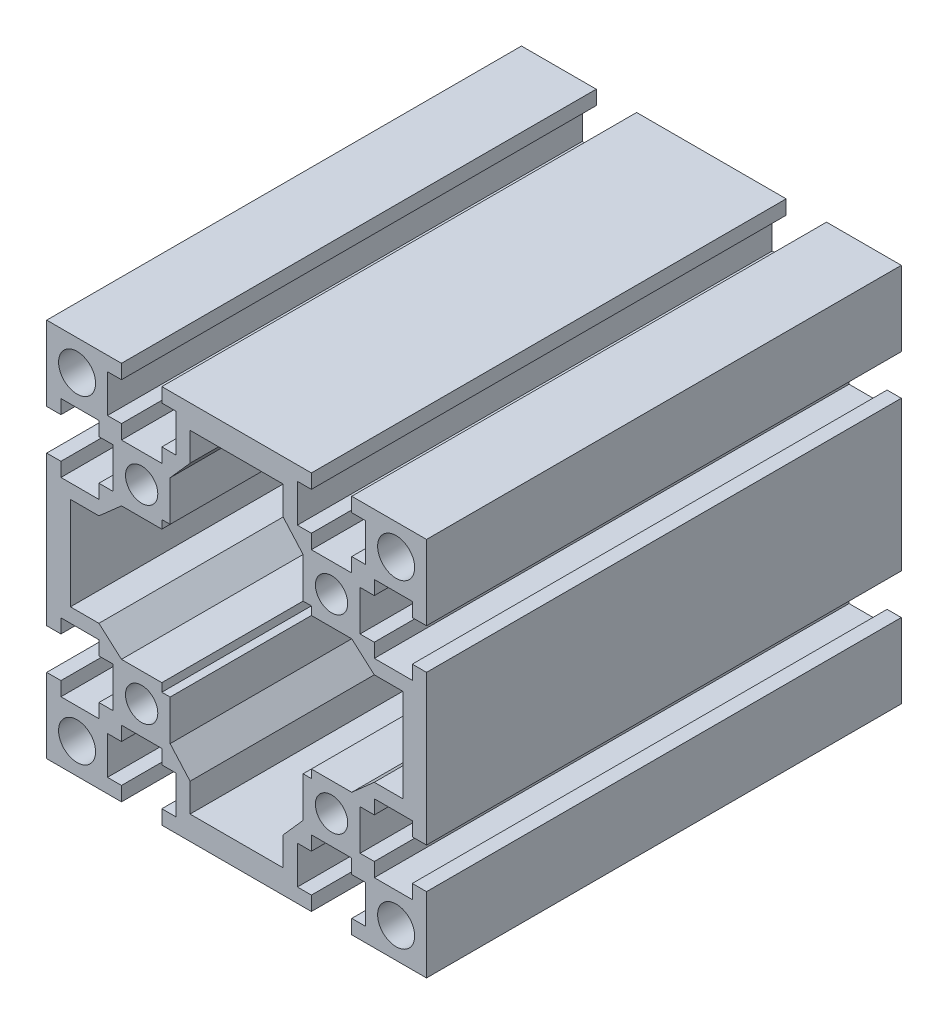
SolidWorks part; units mm, degrees
ref_plane "前视基准面" through (0, 0, 0) normal (0, 0, 1) x (1, 0, 0)
ref_plane "上视基准面" through (0, 0, 0) normal (0, 1, 0) x (1, 0, 0)
ref_plane "右视基准面" through (0, 0, 0) normal (1, 0, 0) x (0, 0, -1)
sketch "草图1" plane through (0, 0, 0) normal (0, 0, 1) x (1, 0, 0)
  line L0 (-23.2188, 39.5458) -> (-38.9688, 39.5458)
  line L1 (-38.9688, 39.5458) -> (-38.9688, 23.7958)
  line L2 (-23.2188, 36.5458) -> (-26.1688, 36.5458)
  line L3 (-35.9688, 26.7458) -> (-35.9688, 23.7958)
  line L4 (-24.9688, 23.7958) -> (-24.9688, 15.2958)
  line L5 (-23.2188, 13.5458) -> (-14.7188, 13.5458)
  line L6 (-12.9688, 15.2958) -> (-12.9688, 23.7958)
  line L7 (-14.7188, 25.5458) -> (-23.2188, 25.5458)
  line L8 (-27.9688, 26.7458) -> (-27.9688, 23.7958)
  line L9 (-23.2188, 28.5458) -> (-26.1688, 28.5458)
  line L10 (-35.9688, 26.7458) -> (-27.9688, 26.7458)
  line L11 (-38.9688, 23.7958) -> (-35.9688, 23.7958)
  line L12 (-27.9688, 23.7958) -> (-24.9688, 23.7958)
  line L13 (-26.1688, 36.5458) -> (-26.1688, 28.5458)
  line L14 (-23.2188, 39.5458) -> (-23.2188, 36.5458)
  line L15 (-23.2188, 28.5458) -> (-23.2188, 25.5458)
  line L16 (-14.7188, 39.5458) -> (1.0312, 39.5458)
  line L17 (-8.7688, 34.5458) -> (10.8312, 34.5458)
  line L18 (-14.7188, 36.5458) -> (-11.7688, 36.5458)
  line L19 (-14.7188, 28.5458) -> (-11.7688, 28.5458)
  line L20 (-11.7688, 36.5458) -> (-11.7688, 28.5458)
  line L21 (-8.7688, 34.5458) -> (-8.7688, 28.5458)
  line L22 (-14.7188, 39.5458) -> (-14.7188, 36.5458)
  line L23 (-14.7188, 28.5458) -> (-14.7188, 25.5458)
  line L24 (-38.9688, -0.4542) -> (-38.9688, 15.2958)
  line L25 (-35.9688, 12.3458) -> (-35.9688, 15.2958)
  line L26 (-27.9688, 12.3458) -> (-27.9688, 15.2958)
  line L27 (-35.9688, 12.3458) -> (-27.9688, 12.3458)
  line L28 (-38.9688, 15.2958) -> (-35.9688, 15.2958)
  line L29 (-27.9688, 15.2958) -> (-24.9688, 15.2958)
  line L30 (16.7812, 39.5458) -> (1.0312, 39.5458)
  line L31 (16.7812, 36.5458) -> (13.8312, 36.5458)
  line L32 (15.0312, 23.7958) -> (15.0312, 15.2958)
  line L33 (16.7812, 13.5458) -> (25.2812, 13.5458)
  line L34 (27.0312, 15.2958) -> (27.0312, 23.7958)
  line L35 (25.2812, 25.5458) -> (16.7812, 25.5458)
  line L36 (16.7812, 28.5458) -> (13.8312, 28.5458)
  line L37 (13.8312, 36.5458) -> (13.8312, 28.5458)
  line L38 (10.8312, 34.5458) -> (10.8312, 28.5458)
  line L39 (16.7812, 39.5458) -> (16.7812, 36.5458)
  line L40 (16.7812, 28.5458) -> (16.7812, 25.5458)
  line L41 (25.2812, 39.5458) -> (41.0312, 39.5458)
  line L42 (41.0312, 39.5458) -> (41.0312, 23.7958)
  line L43 (25.2812, 36.5458) -> (28.2312, 36.5458)
  line L44 (38.0312, 26.7458) -> (38.0312, 23.7958)
  line L45 (30.0312, 26.7458) -> (30.0312, 23.7958)
  line L46 (25.2812, 28.5458) -> (28.2312, 28.5458)
  line L47 (38.0312, 26.7458) -> (30.0312, 26.7458)
  line L48 (41.0312, 23.7958) -> (38.0312, 23.7958)
  line L49 (30.0312, 23.7958) -> (27.0312, 23.7958)
  line L50 (28.2312, 36.5458) -> (28.2312, 28.5458)
  line L51 (25.2812, 39.5458) -> (25.2812, 36.5458)
  line L52 (25.2812, 28.5458) -> (25.2812, 25.5458)
  line L53 (41.0312, -0.4542) -> (41.0312, 15.2958)
  line L54 (38.0312, 12.3458) -> (38.0312, 15.2958)
  line L55 (30.0312, 12.3458) -> (30.0312, 15.2958)
  line L56 (38.0312, 12.3458) -> (30.0312, 12.3458)
  line L57 (41.0312, 15.2958) -> (38.0312, 15.2958)
  line L58 (30.0312, 15.2958) -> (27.0312, 15.2958)
  line L59 (-14.7188, 13.5458) -> (-14.7188, 15.2958)
  line L60 (-12.9688, 15.2958) -> (-14.7188, 15.2958)
  line L61 (16.7812, 13.5458) -> (16.7812, 15.2958)
  line L62 (15.0312, 15.2958) -> (16.7812, 15.2958)
  line L63 (-12.9688, 23.7958) -> (-8.7688, 28.5458)
  line L64 (10.8312, 28.5458) -> (15.0312, 23.7958)
  line L66 (-33.9688, 9.3458) -> (-33.9688, -10.2542)
  line L67 (-33.9688, 9.3458) -> (-27.9688, 9.3458)
  line L68 (-23.2188, -14.4542) -> (-14.7188, -14.4542)
  line L69 (-33.9688, -10.2542) -> (-27.9688, -10.2542)
  line L72 (-12.9688, -16.2042) -> (-14.7188, -16.2042)
  line L73 (-14.7188, -14.4542) -> (-14.7188, -16.2042)
  line L74 (-23.2188, 13.5458) -> (-27.9688, 9.3458)
  line L75 (-27.9688, -10.2542) -> (-23.2188, -14.4542)
  line L76 (36.0312, 9.3458) -> (36.0312, -10.2542)
  line L77 (36.0312, 9.3458) -> (30.0312, 9.3458)
  line L78 (25.2812, -14.4542) -> (16.7812, -14.4542)
  line L79 (36.0312, -10.2542) -> (30.0312, -10.2542)
  line L80 (15.0312, -16.2042) -> (16.7812, -16.2042)
  line L81 (16.7812, -14.4542) -> (16.7812, -16.2042)
  line L82 (25.2812, 13.5458) -> (30.0312, 9.3458)
  line L83 (30.0312, -10.2542) -> (25.2812, -14.4542)
  line L84 (-23.2188, -40.4542) -> (-38.9688, -40.4542)
  line L85 (-38.9688, -40.4542) -> (-38.9688, -24.7042)
  line L86 (-23.2188, -37.4542) -> (-26.1688, -37.4542)
  line L87 (-35.9688, -27.6542) -> (-35.9688, -24.7042)
  line L88 (-24.9688, -24.7042) -> (-24.9688, -16.2042)
  line L89 (-14.7188, -26.4542) -> (-23.2188, -26.4542)
  line L90 (-27.9688, -27.6542) -> (-27.9688, -24.7042)
  line L91 (-23.2188, -29.4542) -> (-26.1688, -29.4542)
  line L92 (-35.9688, -27.6542) -> (-27.9688, -27.6542)
  line L93 (-38.9688, -24.7042) -> (-35.9688, -24.7042)
  line L94 (-27.9688, -24.7042) -> (-24.9688, -24.7042)
  line L95 (-26.1688, -37.4542) -> (-26.1688, -29.4542)
  line L96 (-23.2188, -40.4542) -> (-23.2188, -37.4542)
  line L97 (-23.2188, -29.4542) -> (-23.2188, -26.4542)
  line L98 (-14.7188, -40.4542) -> (1.0312, -40.4542)
  line L99 (-14.7188, -37.4542) -> (-11.7688, -37.4542)
  line L100 (-14.7188, -29.4542) -> (-11.7688, -29.4542)
  line L101 (-11.7688, -37.4542) -> (-11.7688, -29.4542)
  line L102 (-14.7188, -40.4542) -> (-14.7188, -37.4542)
  line L103 (-14.7188, -29.4542) -> (-14.7188, -26.4542)
  line L104 (-38.9688, -0.4542) -> (-38.9688, -16.2042)
  line L105 (-35.9688, -13.2542) -> (-35.9688, -16.2042)
  line L106 (-27.9688, -13.2542) -> (-27.9688, -16.2042)
  line L107 (-35.9688, -13.2542) -> (-27.9688, -13.2542)
  line L108 (-38.9688, -16.2042) -> (-35.9688, -16.2042)
  line L109 (-27.9688, -16.2042) -> (-24.9688, -16.2042)
  line L110 (16.7812, -40.4542) -> (1.0312, -40.4542)
  line L111 (16.7812, -37.4542) -> (13.8312, -37.4542)
  line L112 (27.0312, -16.2042) -> (27.0312, -24.7042)
  line L113 (25.2812, -26.4542) -> (16.7812, -26.4542)
  line L114 (16.7812, -29.4542) -> (13.8312, -29.4542)
  line L115 (13.8312, -37.4542) -> (13.8312, -29.4542)
  line L116 (16.7812, -29.4542) -> (16.7812, -26.4542)
  line L117 (25.2812, -40.4542) -> (41.0312, -40.4542)
  line L118 (41.0312, -40.4542) -> (41.0312, -24.7042)
  line L119 (25.2812, -37.4542) -> (28.2312, -37.4542)
  line L120 (38.0312, -27.6542) -> (38.0312, -24.7042)
  line L121 (30.0312, -27.6542) -> (30.0312, -24.7042)
  line L122 (25.2812, -29.4542) -> (28.2312, -29.4542)
  line L123 (38.0312, -27.6542) -> (30.0312, -27.6542)
  line L124 (41.0312, -24.7042) -> (38.0312, -24.7042)
  line L125 (30.0312, -24.7042) -> (27.0312, -24.7042)
  line L126 (28.2312, -37.4542) -> (28.2312, -29.4542)
  line L127 (25.2812, -40.4542) -> (25.2812, -37.4542)
  line L128 (25.2812, -29.4542) -> (25.2812, -26.4542)
  line L129 (41.0312, -0.4542) -> (41.0312, -16.2042)
  line L130 (38.0312, -13.2542) -> (38.0312, -16.2042)
  line L131 (30.0312, -13.2542) -> (30.0312, -16.2042)
  line L132 (38.0312, -13.2542) -> (30.0312, -13.2542)
  line L133 (41.0312, -16.2042) -> (38.0312, -16.2042)
  line L134 (30.0312, -16.2042) -> (27.0312, -16.2042)
  line L135 (-12.9688, -16.2042) -> (-12.9688, -24.7042)
  line L136 (-8.7688, -35.4542) -> (10.8312, -35.4542)
  line L137 (-8.7688, -35.4542) -> (-8.7688, -29.4542)
  line L138 (15.0312, -24.7042) -> (15.0312, -16.2042)
  line L139 (10.8312, -35.4542) -> (10.8312, -29.4542)
  line L140 (-12.9688, -24.7042) -> (-8.7688, -29.4542)
  line L141 (10.8312, -29.4542) -> (15.0312, -24.7042)
  line L142 (16.7812, -37.4542) -> (16.7812, -40.4542)
  circle A0 centre (-32.5688, 33.1458) radius 3.9
  circle A1 centre (-18.9688, 19.5458) radius 3.4
  circle A2 centre (34.6312, 33.1458) radius 3.9
  circle A3 centre (21.0312, 19.5458) radius 3.4
  circle A4 centre (-32.5688, -34.0542) radius 3.9
  circle A5 centre (-18.9688, -20.4542) radius 3.4
  circle A6 centre (34.6312, -34.0542) radius 3.9
  circle A7 centre (21.0312, -20.4542) radius 3.4
extrude "凸台-拉伸1" add sketch "草图1" along normal blind 100
